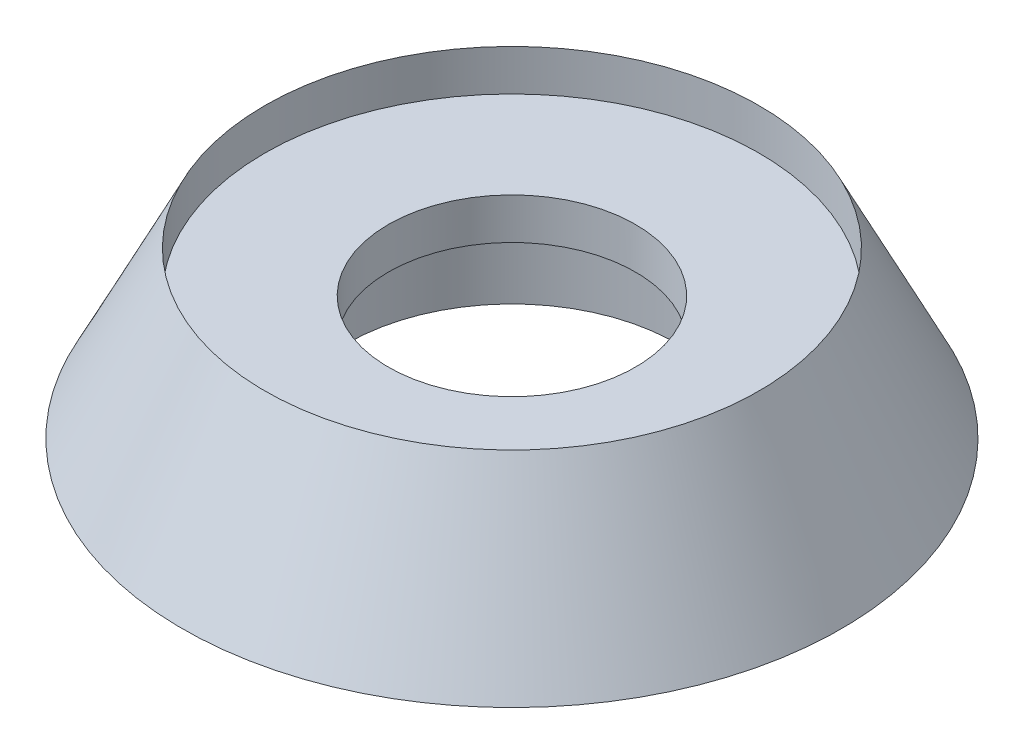
SolidWorks part; units mm, degrees
ref_plane "Alzado" through (0, 0, 0) normal (0, 0, 1) x (1, 0, 0)
ref_plane "Planta" through (0, 0, 0) normal (0, 1, 0) x (1, 0, 0)
ref_plane "Vista lateral" through (0, 0, 0) normal (1, 0, 0) x (0, 0, -1)
sketch "Croquis2" plane through (0, 0, 0) normal (0, 0, 1) x (1, 0, 0)
  line L0 (0, 0) -> (30, 0)
  line L1 (0, 0) -> (0, -20)
  line L2 (0, -20) -> (40, -20)
  line L3 (30, 0) -> (40, -20)
  dimension "D1" = 30
  dimension "D2" = 20
  dimension "D3" = 40
revolve "Revolución1" add sketch "Croquis2" angle 360 about L1
sketch "Croquis3" plane through (0, 0, 0) normal (0, 1, 0) x (1, 0, 0)
  circle A0 centre (0, 0) radius 30
extrude "Cortar-Extruir1" cut sketch "Croquis3" against normal blind 5
sketch "Croquis4" plane through (0, -5, 0) normal (0, 1, 0) x (1, 0, 0)
  circle A0 centre (0, 0) radius 15
  dimension "D1" = 30
extrude "Cortar-Extruir2" cut sketch "Croquis4" against normal through all
sketch "Croquis5" plane through (0, -20, 0) normal (0, -1, 0) x (1, 0, 0)
  circle A0 centre (0, 0) radius 20
  dimension "D1" = 40
extrude "Cortar-Extruir3" cut sketch "Croquis5" against normal blind 10
